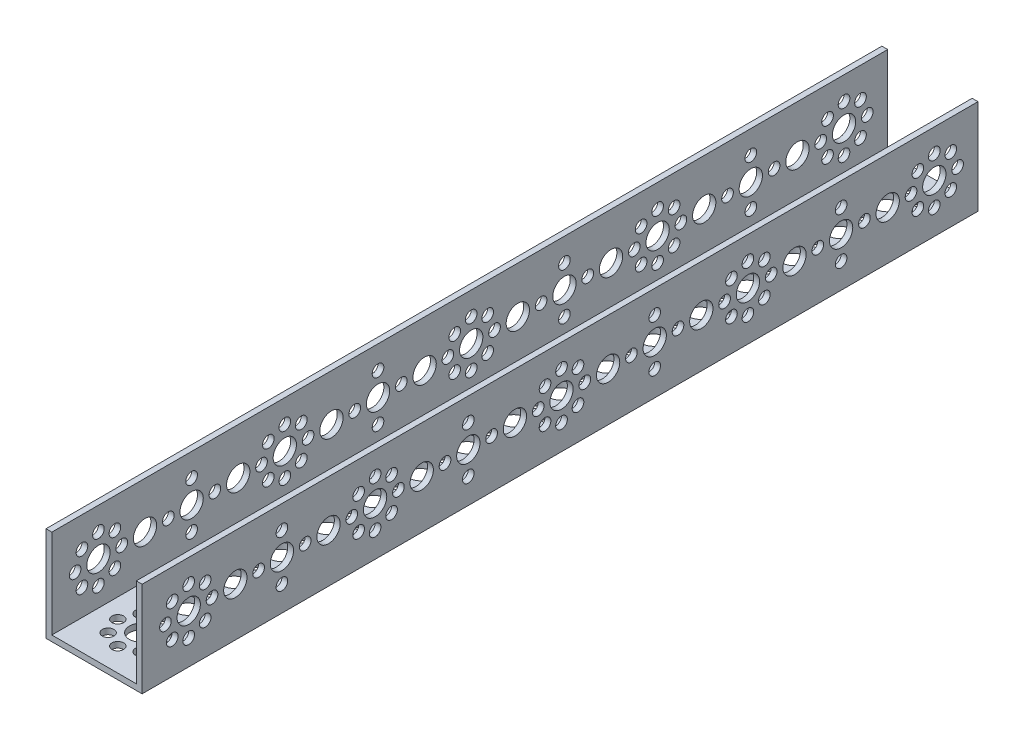
SolidWorks part; units mm, degrees
ref_plane "Front Plane" through (0, 0, 0) normal (0, 0, 1) x (1, 0, 0)
ref_plane "Top Plane" through (0, 0, 0) normal (0, 1, 0) x (1, 0, 0)
ref_plane "Right Plane" through (0, 0, 0) normal (1, 0, 0) x (0, 0, -1)
sketch "Esquisse1" plane through (0, 0, 0) normal (0, 0, 1) x (1, 0, 0)
  line L0 (0, 0) -> (0, 32.6)
  line L1 (0, 32.6) -> (2, 32.6)
  line L2 (2, 32.6) -> (2, 2)
  line L3 (2, 2) -> (31, 2)
  line L4 (31, 2) -> (31, 32.6)
  line L5 (31, 32.6) -> (33, 32.6)
  line L6 (33, 32.6) -> (33, 0)
  line L7 (33, 0) -> (0, 0)
  dimension "D1" = 32.6
  dimension "D2" = 2
  dimension "D3" = 2
  dimension "D4" = 2
  dimension "D5" = 32.6
  dimension "D6" = 33
  dimension "D7" = 29
extrude "Boss.-Extru.1" add sketch "Esquisse1" along normal blind 287
ref_plane "Plan1" through (0, 0, 0) normal (0, -1, 0) x (-1, 0, 0)
sketch "Esquisse2" plane through (0, 0, 0) normal (0, -1, 0) x (-1, 0, 0)
  line L0 (0, -287) -> (-33, -287) construction
  line L1 (-33, -287) -> (-33, 0) construction
  circle A0 centre (-16.65, -271) radius 4
  point P4 (-16.5, -287)
  dimension "D1" = 8
  dimension "D2" = 16
  dimension "D3" = 16.35
extrude "Enlèv. mat.-Extru.1" cut sketch "Esquisse2" against normal through all both and the other way through all
pattern_linear "Répétition linéaire1" count 17 spacing 16 along (0, 0, -1) of "Enlèv. mat.-Extru.1"
sketch "Esquisse3" plane through (0, 0, 0) normal (0, -1, 0) x (1, 0, 0)
  circle A0 centre (24.65, 271) radius 2
  circle A1 centre (16.65, 271) radius 4 construction
  dimension "D1" = 4
  dimension "D2" = 8
  dimension "D3" = 0
extrude "Enlèv. mat.-Extru.2" cut sketch "Esquisse3" against normal through all both and the other way through all contours A0
pattern_circular "Répétition circulaire1" count 4 over 360 about axis through (16.65, 0, 271) along (0, 1, 0) of "Enlèv. mat.-Extru.2"
pattern_circular "Répétition circulaire2" count 8 over 360 about axis through (16.65, 0, 271) along (0, 1, 0) skipping 2, 4, 6 of "Enlèv. mat.-Extru.2"
pattern_linear "Répétition linéaire2" count 17 spacing 16 along (0, 0, -1) skipping (1, 0), (3, 0), (5, 0), (7, 0), (9, 0), (11, 0), (13, 0), (15, 0) of "Répétition circulaire1", "Enlèv. mat.-Extru.2"
pattern_linear "Répétition linéaire3" count 17 spacing 16 along (0, 0, -1) skipping (1, 0), (2, 0), (3, 0), (5, 0), (6, 0), (7, 0), (9, 0), (10, 0), (11, 0), (13, 0), (14, 0), (15, 0) of "Répétition circulaire2"
ref_plane "Plan4" through (31, 0, 0) normal (-1, 0, 0) x (0, 0, 1)
ref_point "Point2" parameters "D1"=29
ref_plane "Plan5" through (0, 0, 0) normal (0.7071, -0.7071, 0) x (0, 0, -1)
mirror "Symétrie2" about plane through (0, 0, 0) normal (0.7071, -0.7071, 0) of "Répétition linéaire3", "Répétition linéaire2", "Répétition circulaire2", "Répétition circulaire1", "Enlèv. mat.-Extru.2", "Répétition linéaire1", "Enlèv. mat.-Extru.1"
